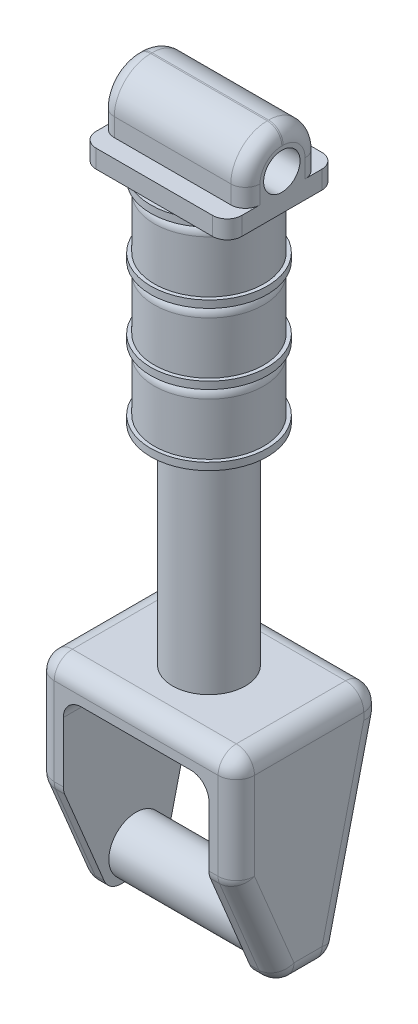
SolidWorks part; units mm, degrees
ref_plane "Front" through (0, 0, 0) normal (0, 0, 1) x (1, 0, 0)
ref_plane "Top" through (0, 0, 0) normal (0, 1, 0) x (1, 0, 0)
ref_plane "Right" through (0, 0, 0) normal (1, 0, 0) x (0, 0, -1)
sketch "Sketch1" plane through (0, 0, 0) normal (0, 0, 1) x (1, 0, 0)
  line L0 (0, -279.4) -> (38.1, -279.4) construction
  line L1 (76.2, -279.4) -> (-76.2, -279.4) construction
  line L2 (76.2, -279.4) -> (76.2, 279.4) construction
  line L3 (76.2, 279.4) -> (-76.2, 279.4) construction
  line L4 (-76.2, -279.4) -> (-76.2, 279.4) construction
  line L5 (76.2, -279.4) -> (-76.2, 279.4) construction
  line L6 (76.2, 279.4) -> (-76.2, -279.4) construction
  line L7 (38.1, -279.4) -> (38.1, -76.2) construction
  line L8 (38.1, -76.2) -> (-38.1, -76.2) construction
  line L9 (-38.1, -76.2) -> (-38.1, -279.4) construction
  line L10 (-38.1, -196.85) -> (-38.1, -158.75) construction
  line L11 (-50.8, -196.85) -> (-69.85, -196.85)
  line L12 (-69.85, -196.85) -> (-69.85, -44.45)
  line L13 (-69.85, -44.45) -> (69.85, -44.45)
  line L14 (69.85, -44.45) -> (69.85, -196.85)
  line L15 (69.85, -196.85) -> (50.8, -196.85)
  line L16 (50.8, -196.85) -> (50.8, -63.5)
  line L17 (50.8, -63.5) -> (-50.8, -63.5)
  line L18 (-50.8, -63.5) -> (-50.8, -196.85)
  point P0 (0, 0)
  dimension "D1" = 558.8
  dimension "D2" = 152.4
  dimension "D3" = 76.2
  dimension "D4" = 203.2
  dimension "D5" = 38.1
  dimension "D6" = 38.1
  dimension "D7" = 19.05
  dimension "D8" = 19.05
  dimension "D9" = 19.05
  dimension "D10" = 12.7
  dimension "D11" = 12.7
  dimension "D12" = 12.7
  dimension "D13" = 82.55
  dimension "D14" = 82.55
extrude "Boss-Extrude1" add sketch "Sketch1" against normal blind 101.6
sketch "Sketch2" plane through (69.85, 0, 0) normal (1, 0, 0) x (0, 0, -1)
  line L0 (101.6, -196.85) -> (0, -196.85) construction
  line L1 (0, -196.85) -> (0, -44.45) construction
  circle A0 centre (50.8, -177.8) radius 19.05
  dimension "D1" = 38.1
  dimension "D2" = 19.05
  dimension "D3" = 50.8
extrude "Boss-Extrude2" add sketch "Sketch2" against normal up to surface (120.65 mm away) up to face at (-50.8, -130.175, -50.8)
sketch "Sketch4" plane through (69.85, 0, 0) normal (1, 0, 0) x (0, 0, -1)
  line L0 (31.75, -196.85) -> (69.85, -196.85)
  line L1 (101.6, -196.85) -> (0, -196.85) construction
  line L3 (101.6, -196.85) -> (101.6, -44.45) construction
  line L4 (101.6, -63.5) -> (101.6, -196.85)
  line L5 (101.6, -196.85) -> (69.85, -196.85)
  line L6 (50.8, -44.45) -> (50.8, -233.0017) construction
  line L7 (101.6, -44.45) -> (0, -44.45) construction
  line L8 (69.85, -196.85) -> (101.6, -63.5)
  line L9 (31.75, -196.85) -> (0, -120.65)
  line L10 (0, -196.85) -> (0, -44.45) construction
  line L11 (0, -120.65) -> (0, -196.85)
  line L12 (0, -196.85) -> (31.75, -196.85)
  line M6 (0, -44.45) -> (0, -196.85)
  line M7 (0, -196.85) -> (101.6, -196.85)
  line M8 (101.6, -196.85) -> (101.6, -44.45)
  dimension "D1" = 38.1
  dimension "D2" = 31.75
  dimension "D3" = 19.05
extrude "Cut-Extrude1" cut sketch "Sketch4" against normal up to surface (139.7 mm away) contours L9 M7 M6 | L8 M7 M8 up to face at (-69.85, -120.65, -50.8)
fillet "Fillet1" radius 12.7 10 edges at (-50.8, -63.5, -50.8) (50.8, -63.5, -50.8) (0, -44.45, 0) (0, -44.45, -101.6) (60.325, -196.85, -31.75) (60.325, -196.85, -69.85) (-60.325, -196.85, -69.85) (-60.325, -196.85, -31.75) (-60.325, -120.65, 0) (60.325, -120.65, 0)
fillet "Fillet2" radius 12.7 22 edges at (-69.85, -120.6007, -0.2466) (-69.85, -156.0146, -14.7353) (-69.85, -194.717, -33.172) (-69.85, -196.85, -50.0177) (-69.85, -194.1161, -67.6906) (-69.85, -125.2958, -86.8867) (-69.85, -60.325, -101.6) (-69.85, -48.1697, -97.8803) (-69.85, -44.45, -50.8) (-69.85, -48.1697, -3.7197) (-69.85, -87.63, 0) (69.85, -48.1697, -97.8803) (69.85, -60.325, -101.6) (69.85, -125.2958, -86.8867) (69.85, -194.1161, -67.6906) (69.85, -196.85, -50.0177) (69.85, -194.717, -33.172) (69.85, -156.0146, -14.7353) (69.85, -120.6007, -0.2466) (69.85, -87.63, 0) (69.85, -48.1697, -3.7197) (69.85, -44.45, -50.8)
sketch "Sketch5" plane through (0, -44.45, 0) normal (0, 1, 0) x (1, 0, 0)
  circle A0 centre (0, 50.8) radius 25.4
  dimension "D1" = 50.8
extrude "Boss-Extrude3" add sketch "Sketch5" along normal blind 146.05
sketch "Sketch6" plane through (0, 101.6, 0) normal (0, 1, 0) x (1, 0, 0)
  circle A0 centre (0, 50.8) radius 40.64
  dimension "D1" = 81.28
extrude "Boss-Extrude4" add sketch "Sketch6" along normal blind 5.08
sketch "Sketch7" plane through (0, 106.68, 0) normal (0, 1, 0) x (1, 0, 0)
  circle A0 centre (0, 50.8) radius 38.1
  dimension "D1" = 76.2
extrude "Boss-Extrude5" add sketch "Sketch7" along normal blind 43.942
fillet "Fillet5" radius 7.62 1 edges at (0, 150.622, -12.7)
sketch "Sketch8" plane through (0, 150.622, 0) normal (0, 1, 0) x (1, 0, 0)
  circle A0 centre (0, 50.8) radius 40.64
  dimension "D1" = 81.28
extrude "Boss-Extrude6" add sketch "Sketch8" along normal blind 5.08
sketch "Sketch9" plane through (0, 155.702, 0) normal (0, 1, 0) x (1, 0, 0)
  circle A0 centre (0, 50.8) radius 38.1
  dimension "D1" = 76.2
extrude "Boss-Extrude7" add sketch "Sketch9" along normal blind 43.942
fillet "Fillet6" radius 7.62 1 edges at (0, 199.644, -12.7)
sketch "Sketch10" plane through (0, 199.644, 0) normal (0, 1, 0) x (1, 0, 0)
  circle A0 centre (0, 50.8) radius 40.64
  dimension "D1" = 81.28
extrude "Boss-Extrude8" add sketch "Sketch10" along normal blind 5.08
sketch "Sketch11" plane through (0, 204.724, 0) normal (0, 1, 0) x (1, 0, 0)
  circle A0 centre (0, 50.8) radius 38.1
  dimension "D1" = 76.2
extrude "Boss-Extrude9" add sketch "Sketch11" along normal blind 43.942
fillet "Fillet7" radius 7.62 1 edges at (0, 248.666, -12.7)
sketch "Sketch12" plane through (0, 248.666, 0) normal (0, 1, 0) x (1, 0, 0)
  circle A0 centre (0, 50.8) radius 40.64
  dimension "D1" = 81.28
extrude "Boss-Extrude10" add sketch "Sketch12" along normal blind 5.08
sketch "Sketch13" plane through (0, 0, 0) normal (1, 0, 0) x (0, 0, -1)
  line L0 (50.8, 253.746) -> (12.7, 253.746)
  line L1 (91.44, 253.746) -> (10.16, 253.746) construction
  line L2 (12.7, 253.746) -> (12.7, 266.446)
  line L3 (12.7, 266.446) -> (25.4, 266.446)
  line L4 (25.4, 266.446) -> (25.4, 279.146)
  line L5 (50.8, 304.546) -> (51.7783, 304.546)
  line L6 (77.1783, 279.146) -> (77.1783, 266.446)
  line L7 (77.1783, 266.446) -> (88.9, 266.446)
  line L8 (88.9, 266.446) -> (88.9, 253.746)
  line L9 (88.9, 253.746) -> (50.8, 253.746)
  line L10 (50.8, 253.746) -> (50.8, 279.146) construction
  circle A0 centre (50.8, 279.146) radius 12.7
  arc A1 (50.8, 304.546) -> (25.4, 279.146) centre (50.8, 279.146) ccw
  arc A2 (77.1783, 279.146) -> (51.7783, 304.546) centre (51.7783, 279.146) ccw
  point P15 (25.4, 304.546)
extrude "Boss-Extrude11" add sketch "Sketch13" along normal blind 50.8 and the other way blind 50.8
fillet "Fillet3" radius 10.16 4 edges at (50.8, 260.096, -12.7) (-50.8, 260.096, -12.7) (-50.8, 260.096, -88.9) (50.8, 260.096, -88.9)
fillet "Fillet4" radius 10.16 10 edges at (-50.8, 272.796, -77.1783) (-50.8, 272.796, -25.4) (-50.8, 297.1065, -32.8395) (-50.8, 304.546, -51.2891) (50.8, 272.796, -77.1783) (50.8, 297.1065, -69.7388) (50.8, 304.546, -51.2891) (50.8, 272.796, -25.4) (-50.8, 297.1065, -69.7388) (50.8, 297.1065, -32.8395)
